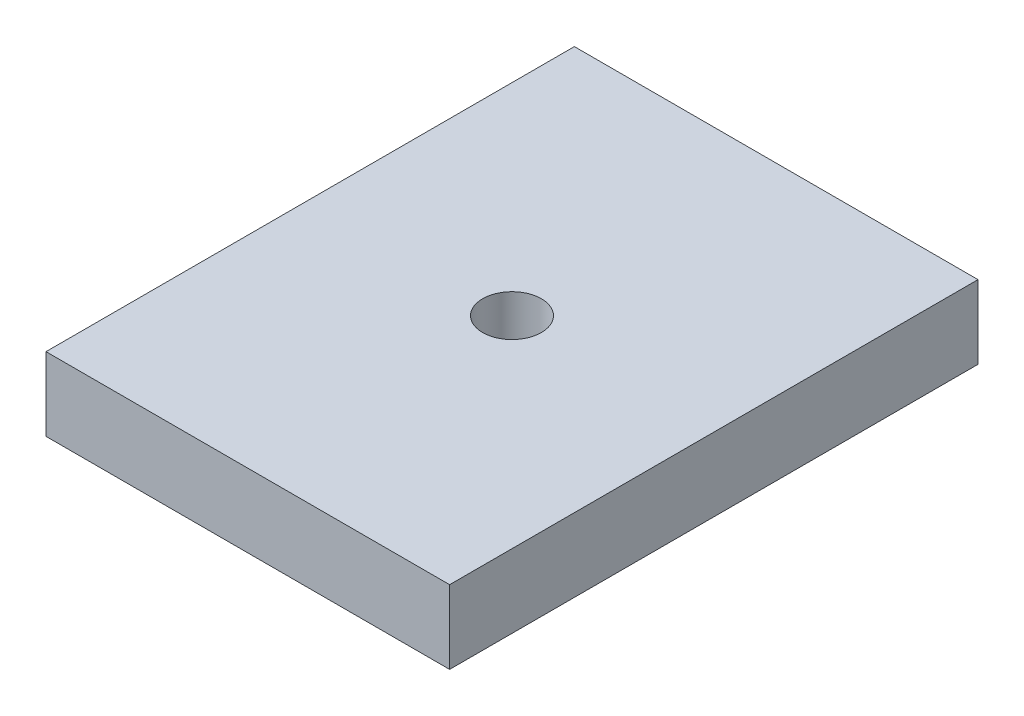
SolidWorks part; units mm, degrees
ref_plane "Front Plane" through (0, 0, 0) normal (0, 0, 1) x (1, 0, 0)
ref_plane "Top Plane" through (0, 0, 0) normal (0, 1, 0) x (1, 0, 0)
ref_plane "Right Plane" through (0, 0, 0) normal (1, 0, 0) x (0, 0, -1)
sketch "Sketch2" plane through (0, 0, 0) normal (0, 1, 0) x (1, 0, 0)
  line L0 (27.5, 36) -> (27.5, -36.0006)
  line L1 (-27.5001, -36.0006) -> (27.5, -36.0006)
  line L2 (-27.5001, -36.0006) -> (-27.5001, 36)
  line L3 (27.5, 36) -> (-27.5001, 36)
  circle A0 centre (0, 0) radius 4
  point P6 (0, 0)
  dimension "D3" = 8
  dimension "D1" = 72.0006
  dimension "D2" = 55.0001
  dimension "D4" = 36
  dimension "D5" = 27.5
extrude "Boss-Extrude1" add sketch "Sketch2" along normal blind 10
